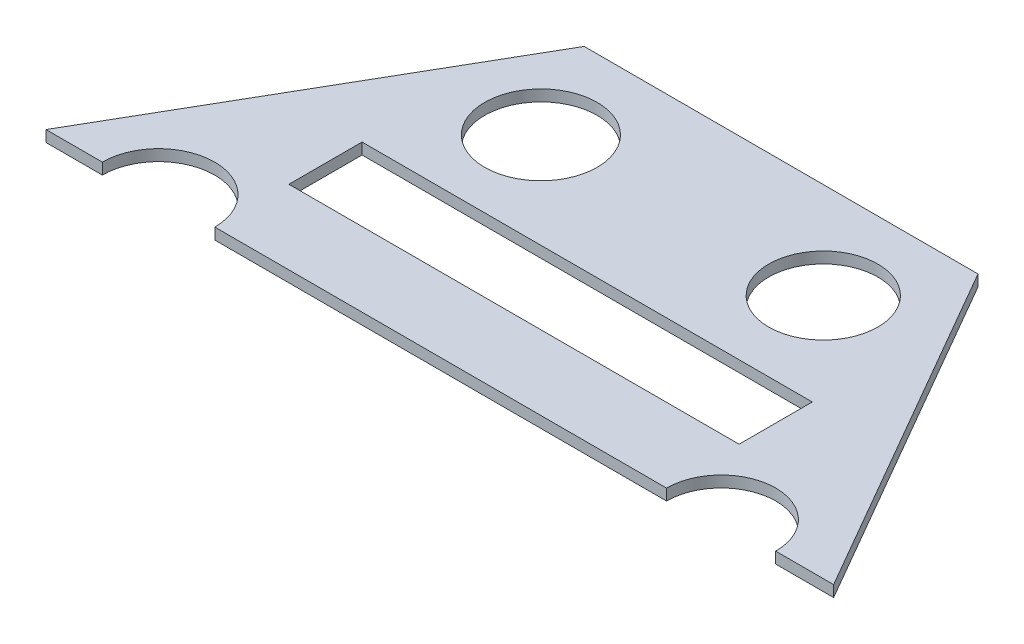
SolidWorks part; units mm, degrees
ref_plane "Front Plane" through (0, 0, 0) normal (0, 0, 1) x (1, 0, 0)
ref_plane "Top Plane" through (0, 0, 0) normal (0, 1, 0) x (1, 0, 0)
ref_plane "Right Plane" through (0, 0, 0) normal (1, 0, 0) x (0, 0, -1)
sketch "Sketch1" plane through (0, 0, 0) normal (0, 1, 0) x (1, 0, 0)
  line L19 (175.1018, 303.0501) -> (-174.8982, 303.1676)
  line L20 (-174.8982, 303.1676) -> (-350, 0.1175)
  line L21 (-350, 0.1175) -> (-175.1018, -303.0501)
  line L22 (-175.1018, -303.0501) -> (174.8982, -303.1676)
  line L23 (174.8982, -303.1676) -> (350, -0.1175)
  line L24 (350, -0.1175) -> (175.1018, 303.0501)
  circle A4 centre (0, 0) radius 350 construction
  dimension "D1" = 700
extrude "Boss-Extrude1" add sketch "Sketch1" along normal blind 10
sketch "Sketch2" plane through (0, 10, 0) normal (0, 1, 0) x (1, 0, 0)
  line L2 (-150, -3.0585) -> (-150, 15)
  line L3 (-150, 15) -> (150, 15)
  line L4 (150, -0.0504) -> (150, 15)
  line L5 (-30.9849, -3.0985) -> (150, 15) construction
  line L6 (-150, 15) -> (31.1936, -3.1194) construction
  line L9 (-175.1018, -303.0501) -> (174.8982, -303.1676)
  line L14 (-175.1018, -303.0501) -> (-350, 0.1175)
  line L15 (-350, 0.1175) -> (350, -0.1175)
  line L16 (350, -0.1175) -> (174.8982, -303.1676)
  point P11 (0, 0)
  dimension "D5" = 300
sketch "Sketch3" plane through (0, 10, 0) normal (0, 1, 0) x (1, 0, 0)
  line L0 (0, 0) -> (0, 200.9503) construction
  line L1 (-200, 65.9137) -> (200, 65.9137)
  line L2 (-200, 65.9137) -> (-200, 130.9137)
  line L3 (-200, 130.9137) -> (200, 130.9137)
  line L4 (200, 65.9137) -> (200, 130.9137)
  line L5 (-200, 65.9137) -> (200, 130.9137) construction
  line L6 (-200, 130.9137) -> (200, 65.9137) construction
  circle A0 centre (250, 0) radius 48.5
  circle A1 centre (-250, 0.0412) radius 50
  circle A3 centre (-126.0766, 215.8954) radius 50
  circle A5 centre (122.9968, 217.6975) radius 48.5
  point P0 (0, 0)
  dimension "D3" = 200
  dimension "D1" = 400
  dimension "D2" = 65
extrude "Cut-Extrude3" cut sketch "Sketch3" against normal blind 10
extrude "Cut-Extrude4" cut sketch "Sketch2" against normal blind 10
